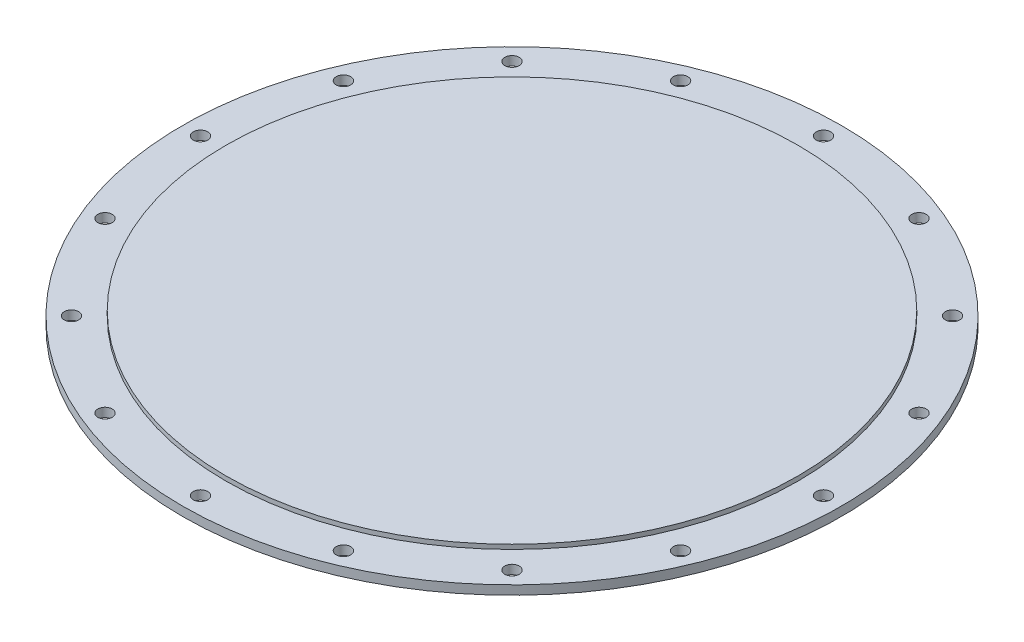
SolidWorks part; units mm, degrees
material "AISI 316 Annealed Stainless Steel Bar (SS)"
ref_plane "Front Plane" through (0, 0, 0) normal (0, 0, 1) x (1, 0, 0)
ref_plane "Top Plane" through (0, 0, 0) normal (0, 1, 0) x (1, 0, 0)
ref_plane "Right Plane" through (0, 0, 0) normal (1, 0, 0) x (0, 0, -1)
sketch "Sketch1" plane through (0, 0, 0) normal (1, 0, 0) x (0, 0, -1)
  line L0 (-365, 19.996) -> (-365, 9.996)
  line L1 (-365, 9.996) -> (0, 9.996)
  line L2 (0, 9.996) -> (0, 24.996)
  line L13 (-317, 19.996) -> (-365, 19.996)
  line L14 (0, 9.996) -> (0, 24.996) construction
  line L22 (0, 24.996) -> (0, -23.4696) construction
  line L24 (0, 24.996) -> (-317, 24.996)
  line L25 (-317, 24.996) -> (-317, 19.996)
  dimension "D1" = 730
  dimension "D8" = 10
revolve "Revolve1" add sketch "Sketch1" angle 360 about L14
sketch "Sketch2" plane through (0, 19.996, 0) normal (0, 1, 0) x (1, 0, 0)
  line L0 (0, -1000) -> (0, 49000) construction
  line L1 (-406.5422, 0) -> (374.3408, 0) construction
  circle A0 centre (0, 345) radius 8
  circle A1 centre (132.0258, 318.7384) radius 8
  circle A2 centre (243.9518, 243.9518) radius 8
  circle A3 centre (318.7384, 132.0258) radius 8
  circle A4 centre (345, 0) radius 8
  circle A5 centre (318.7384, -132.0258) radius 8
  circle A6 centre (243.9518, -243.9518) radius 8
  circle A7 centre (132.0258, -318.7384) radius 8
  circle A8 centre (0, -345) radius 8
  circle A9 centre (-132.0258, -318.7384) radius 8
  circle A10 centre (-243.9518, -243.9518) radius 8
  circle A11 centre (-318.7384, -132.0258) radius 8
  circle A12 centre (-345, 0) radius 8
  circle A13 centre (-318.7384, 132.0258) radius 8
  circle A14 centre (-243.9518, 243.9518) radius 8
  circle A15 centre (-132.0258, 318.7384) radius 8
  point P42 (0, 0)
  dimension "D2" = 16
  dimension "D1" = 345
  dimension "D3" = 16
extrude "Cut-Extrude1" cut sketch "Sketch2" against normal through all
